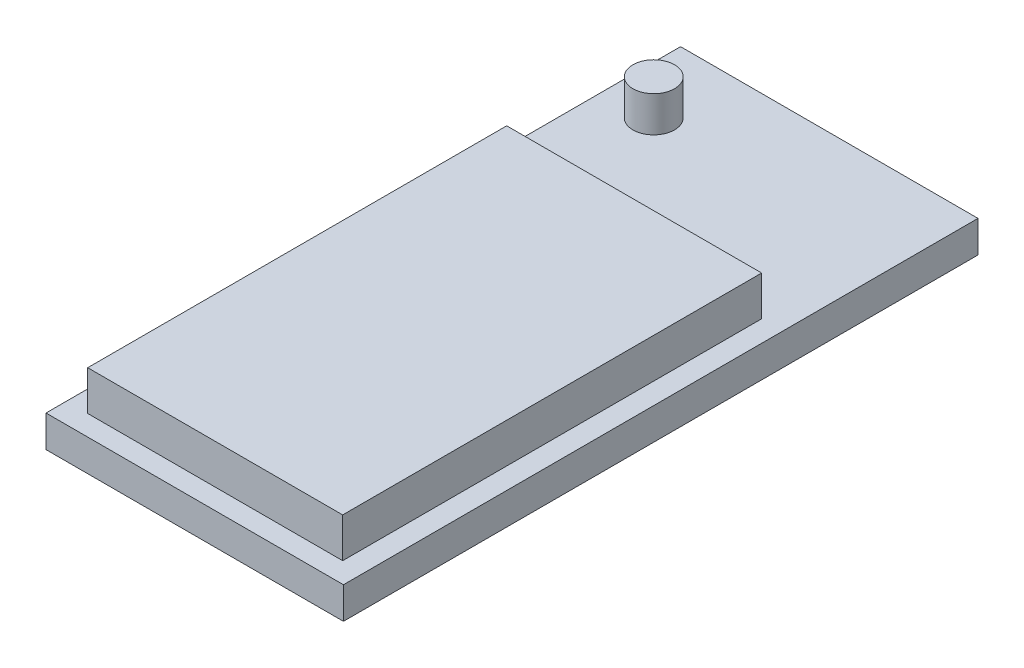
SolidWorks part; units mm, degrees
ref_plane "前视基准面" through (0, 0, 0) normal (0, 0, 1) x (1, 0, 0)
ref_plane "上视基准面" through (0, 0, 0) normal (0, 1, 0) x (1, 0, 0)
ref_plane "右视基准面" through (0, 0, 0) normal (1, 0, 0) x (0, 0, -1)
sketch "草图1" plane through (0, 0, 0) normal (0, 1, 0) x (1, 0, 0)
  line L0 (0, 25.18) -> (0, -27.0638) construction
  line L1 (-7.5, 16) -> (7.5, 16)
  line L2 (-7.5, 16) -> (-7.5, -16)
  line L3 (-7.5, -16) -> (7.5, -16)
  line L4 (7.5, 16) -> (7.5, -16)
  line L5 (-16.4583, 0) -> (20.9944, 0) construction
  dimension "D1" = 15
  dimension "D2" = 32
extrude "凸台-拉伸1" add sketch "草图1" along normal blind 1.6
sketch "草图2" plane through (0, 1.6, 0) normal (0, 1, 0) x (1, 0, 0)
  line L1 (6.4306, -14.97) -> (-6.4265, -14.97)
  line L2 (6.4306, -14.97) -> (6.4306, 6.1588)
  line L3 (6.4306, 6.1588) -> (-6.4265, 6.1588)
  line L4 (-6.4265, -14.97) -> (-6.4265, 6.1588)
extrude "凸台-拉伸2" add sketch "草图2" along normal blind 2
sketch "草图3" plane through (0, 1.6, 0) normal (0, 1, 0) x (1, 0, 0)
  circle A0 centre (-5.0628, 12.21) radius 1.0487
extrude "凸台-拉伸3" add sketch "草图3" along normal blind 1.8
